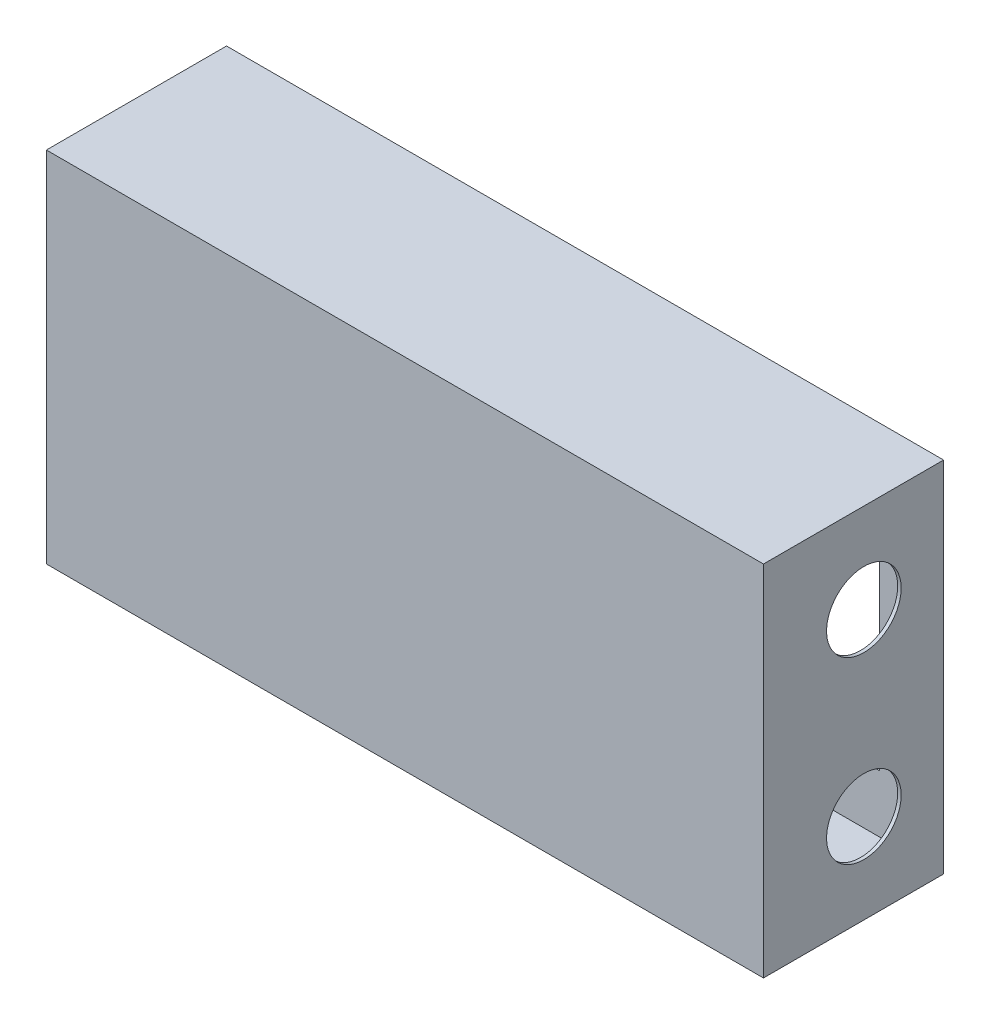
SolidWorks part; units mm, degrees
ref_plane "前视基准面" through (0, 0, 0) normal (0, 0, 1) x (1, 0, 0)
ref_plane "上视基准面" through (0, 0, 0) normal (0, 1, 0) x (1, 0, 0)
ref_plane "右视基准面" through (0, 0, 0) normal (1, 0, 0) x (0, 0, -1)
sketch "草图1" plane through (0, 0, 0) normal (0, 0, 1) x (1, 0, 0)
  line L0 (-125, -62.5) -> (-125, 62.5)
  line L1 (-125, -62.5) -> (125, -62.5)
  line L2 (-125, 62.5) -> (125, 62.5)
  line L3 (125, -62.5) -> (125, 62.5)
  line L4 (-125, -62.5) -> (125, 62.5) construction
  line L5 (-125, 62.5) -> (125, -62.5) construction
  point P1 (0, 0)
  dimension "D1" = 250
  dimension "D2" = 125
extrude "凸台-拉伸1" add sketch "草图1" along normal blind 74.8
sketch "草图2" plane through (0, 0, 0) normal (0, 0, 1) x (1, 0, 0)
  line L0 (-125, 62.5) -> (-125, -62.5) construction
  line L1 (-125, -62.5) -> (125, -62.5) construction
  line L2 (125, -62.5) -> (125, 62.5) construction
  line L3 (125, 62.5) -> (-125, 62.5) construction
  line L4 (-125, 62.5) -> (-125, -62.5)
  line L5 (-125, -62.5) -> (125, -62.5)
  line L6 (125, -62.5) -> (125, 62.5)
  line L7 (125, 62.5) -> (-125, 62.5)
  line L8 (105, 42.5) -> (-105, 42.5)
  line L9 (-105, 42.5) -> (-105, -42.5)
  line L10 (-105, -42.5) -> (105, -42.5)
  line L11 (105, -42.5) -> (105, 42.5)
  dimension "D1" = 20
extrude "切除-拉伸1" cut sketch "草图2" along normal blind 12
sketch "草图3" plane through (0, 0, 0) normal (0, 0, 1) x (1, 0, 0)
  line L4 (105, 42.5) -> (-105, 42.5)
  line L5 (-105, 42.5) -> (-105, -42.5)
  line L6 (-105, -42.5) -> (105, -42.5)
  line L7 (105, -42.5) -> (105, 42.5)
  line L8 (105, 42.5) -> (-105, 42.5)
  line L9 (-105, 42.5) -> (-105, -42.5)
  line L10 (-105, -42.5) -> (105, -42.5)
  line L11 (105, -42.5) -> (105, 42.5)
  dimension "D1" = 0
extrude "凸台-拉伸2" add sketch "草图3" against normal blind 4 draft 45 draft outward yes
shell "抽壳1" thickness 1.2
sketch "草图12" plane through (-125, 0, 0) normal (-1, 0, 0) x (0, 0, 1)
  line L1 (12, 0) -> (74.8, 0) construction
  line L2 (39.8, 62.5) -> (39.8, -62.5)
  line L3 (39.8, 62.5) -> (39.8, -62.5) construction
  line L4 (12, 62.5) -> (12, -62.5) construction
  line L5 (74.8, 62.5) -> (74.8, -62.5) construction
  circle A0 centre (39.8, 0) radius 13
  dimension "D2" = 26
  dimension "D1" = 35
extrude "切除-拉伸3" cut sketch "草图12" against normal up to next
sketch "草图13" plane through (125, 0, 0) normal (1, 0, 0) x (0, 0, -1)
  line L1 (-74.8, 0) -> (28.0444, 0) construction
  line L2 (-39.8, -62.5) -> (-39.8, 62.5)
  line L3 (-39.8, -62.5) -> (-39.8, 62.5) construction
  line L4 (-74.8, -62.5) -> (-74.8, 62.5) construction
  line L6 (-74.8, -31.25) -> (28.0444, -31.25) construction
  line L7 (-74.8, 31.25) -> (28.0444, 31.25) construction
  circle A0 centre (-39.8, 31.25) radius 13
  circle A1 centre (-39.8, -31.25) radius 13
  dimension "D4" = 26
  dimension "D1" = 35
  dimension "D2" = 31.25
  dimension "D3" = 31.25
extrude "切除-拉伸4" cut sketch "草图13" against normal blind 94
ref_plane "基准面1" through (0, 0, 73.6) normal (0, 0, -1) x (-1, 0, 0)
sketch "草图14" plane through (0, 0, 73.6) normal (0, 0, -1) x (-1, 0, 0)
  line L0 (0, 0) -> (400, 0) construction
  line L1 (515, -42.5) -> (515, 42.5)
  line L2 (515, -42.5) -> (285, -42.5)
  line L3 (515, 42.5) -> (285, 42.5)
  line L4 (285, -42.5) -> (285, 42.5)
  line L5 (515, -42.5) -> (285, 42.5) construction
  line L6 (515, 42.5) -> (285, -42.5) construction
  dimension "D1" = 400
  dimension "D2" = 230
  dimension "D3" = 85
extrude "凸台-拉伸3" add sketch "草图14" along normal blind 15 separate body
shell "抽壳2" thickness 1.2
move or copy body "实体-移动/复制1" bodies to move or copy 112 copy no translate (400, 0, 0)
